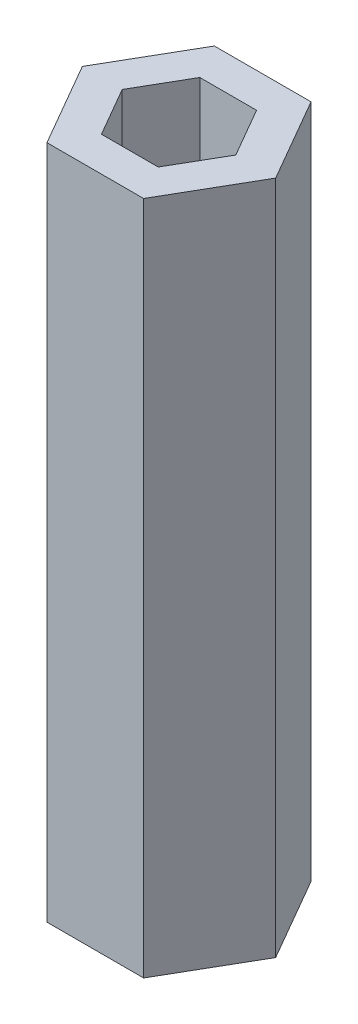
SolidWorks part; units mm, degrees
ref_plane "Front Plane" through (0, 0, 0) normal (0, 0, 1) x (1, 0, 0)
ref_plane "Top Plane" through (0, 0, 0) normal (0, 1, 0) x (1, 0, 0)
ref_plane "Right Plane" through (0, 0, 0) normal (1, 0, 0) x (0, 0, -1)
sketch "Sketch1" plane through (0, 0, 0) normal (0, 1, 0) x (1, 0, 0)
  line L1 (2.1362, 3.7) -> (-2.1362, 3.7)
  line L2 (-2.1362, 3.7) -> (-4.2724, 0)
  line L3 (-4.2724, 0) -> (-2.1362, -3.7)
  line L4 (-2.1362, -3.7) -> (2.1362, -3.7)
  line L5 (2.1362, -3.7) -> (4.2724, 0)
  line L6 (4.2724, 0) -> (2.1362, 3.7)
  line L7 (-3.6373, 6.3) -> (-7.2746, 0)
  line L8 (-7.2746, 0) -> (-3.6373, -6.3)
  line L9 (-3.6373, -6.3) -> (3.6373, -6.3)
  line L10 (3.6373, -6.3) -> (7.2746, 0)
  line L11 (7.2746, 0) -> (3.6373, 6.3)
  line L12 (3.6373, 6.3) -> (-3.6373, 6.3)
  circle A0 centre (0, 0) radius 3.7 construction
  circle A1 centre (0, 0) radius 6.3 construction
  dimension "D1" = 7.4
  dimension "D2" = 12.6
extrude "Boss-Extrude1" add sketch "Sketch1" along normal blind 50.8
